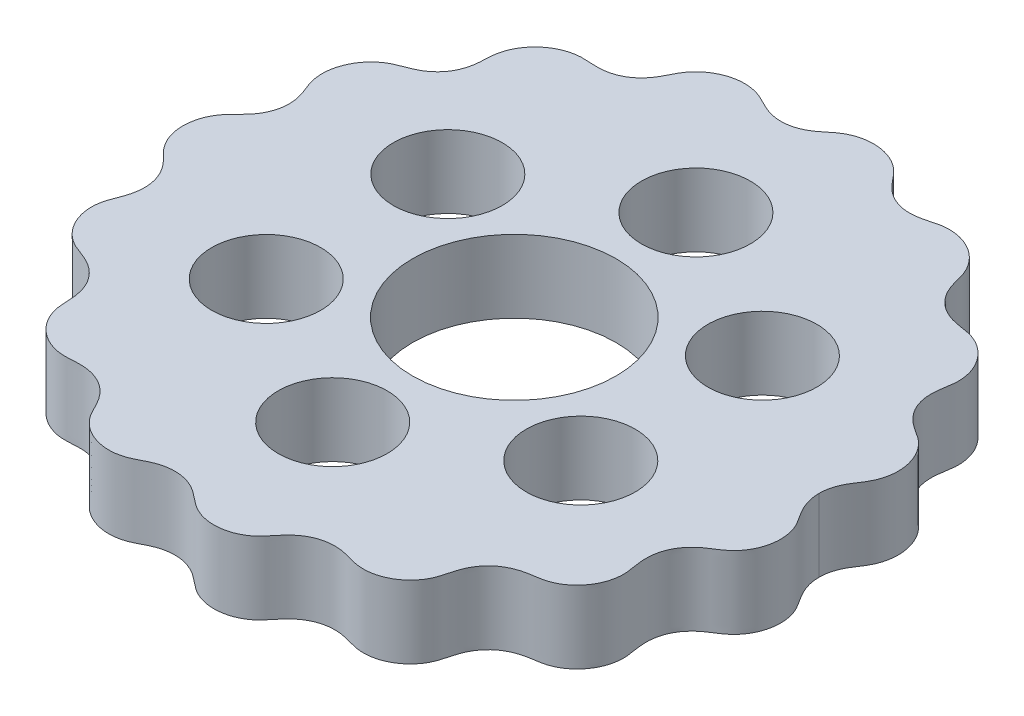
SolidWorks part; units mm, degrees
ref_plane "Front Plane" through (0, 0, 0) normal (0, 0, 1) x (1, 0, 0)
ref_plane "Top Plane" through (0, 0, 0) normal (0, 1, 0) x (1, 0, 0)
ref_plane "Right Plane" through (0, 0, 0) normal (1, 0, 0) x (0, 0, -1)
sketch "Sketch1" plane through (0, 0, 0) normal (0, 1, 0) x (1, 0, 0)
  spline S0 degree 4 poles (43.5597, 11.939) (43.7746, 11.6419) (44.1574, 11.0136) (44.5794, 10) (44.8033, 8.7434) (44.7975, 7.6608) (44.668, 6.827) (44.5095, 6.2289) (44.3102, 5.693) (44.0854, 5.2184) (43.8238, 4.7634) (43.5372, 4.324) (43.2453, 3.8884) (42.9654, 3.4447) (42.7296, 3.0237) (42.5376, 2.6274) (42.385, 2.2599) (42.266, 1.9245) (42.1655, 1.5834) (42.0842, 1.2366) (42.0304, 0.9309) (41.9969, 0.6642) (41.9795, 0.469) (41.9711, 0.3334) (41.9653, 0.1906) (41.9619, 0.0399) (41.9621, -0.0597) (41.9663, -0.2247) (41.9727, -0.3607) (41.9796, -0.4641) (41.9903, -0.5896) (42.0065, -0.7401) (42.0302, -0.9175) (42.0639, -1.118) (42.1042, -1.3174) (42.1625, -1.565) (42.2729, -1.9567) (42.4635, -2.4837) (42.7848, -3.1521) (43.2401, -3.8949) (43.7542, -4.6311) (44.2177, -5.4363) (44.5943, -6.4162) (44.8138, -7.5661) (44.8049, -8.865) (44.4957, -10.2551) (43.9377, -11.4628) (43.2043, -12.4546) (42.4647, -13.1309) (41.8318, -13.5688) (41.1811, -13.9778) (40.4339, -14.4637) (39.5457, -15.1906) (38.6597, -16.2863) (38.0157, -17.6823) (37.7592, -19.0784) (37.7936, -20.3757) (37.9921, -21.5309) (38.1706, -22.571) (38.1712, -23.7387) (37.9208, -24.9899) (37.3737, -26.2495) (36.6163, -27.2891) (35.8251, -28.0387) (35.0302, -28.5952) (34.2607, -28.9947) (33.3665, -29.3001) (32.3631, -29.4635) (31.4228, -29.5881) (30.5606, -29.7939) (29.7901, -30.0721) (29.1146, -30.4094) (28.3277, -30.9283) (27.4937, -31.6997) (26.786, -32.6963) (26.2692, -33.8909) (25.9676, -35.0401) (25.7097, -36.0924) (25.2353, -37.1812) (24.4955, -38.2338) (23.4754, -39.1756) (22.1893, -39.9181) (20.8637, -40.3306) (19.5822, -40.445) (18.4021, -40.3115) (17.3619, -40.0086) (16.2157, -39.6953) (14.9229, -39.5454) (13.5166, -39.678) (12.0834, -40.1877) (10.9215, -40.9607) (10.0286, -41.8586) (9.4107, -42.658) (8.9336, -43.2515) (8.4024, -43.7976) (7.7352, -44.3511) (6.7827, -44.906) (5.5039, -45.3361) (4.0459, -45.4914) (2.6815, -45.3353) (1.4727, -44.9266) (0.4618, -44.3422) (-0.3498, -43.6676) (-1.2509, -42.9181) (-2.3572, -42.2396) (-3.6945, -41.7638) (-5.2255, -41.6235) (-6.6175, -41.8429) (-7.6911, -42.2486) (-8.4854, -42.6528) (-9.165, -43.0118) (-9.8606, -43.341) (-10.8162, -43.6433) (-12.0419, -43.7826) (-13.3808, -43.6607) (-14.7658, -43.2208) (-15.9365, -42.5421) (-16.8664, -41.7061) (-17.4732, -40.8976) (-17.847, -40.2239) (-18.1868, -39.5337) (-18.5964, -38.7239) (-19.2403, -37.7358) (-20.2734, -36.7101) (-21.6552, -35.9123) (-23.06, -35.5304) (-24.2377, -35.4669) (-25.1438, -35.517) (-25.9114, -35.5679) (-26.6817, -35.5811) (-27.6854, -35.4598) (-28.8743, -35.0725) (-30.0474, -34.398) (-31.1208, -33.4185) (-31.8959, -32.3199) (-32.3881, -31.1887) (-32.6041, -30.21) (-32.6668, -29.443) (-32.6957, -28.675) (-32.7429, -27.785) (-32.9283, -26.6523) (-33.4342, -25.3372) (-34.3212, -24.0814) (-35.402, -23.1612) (-36.5427, -22.5423) (-37.6423, -22.1367) (-38.6323, -21.7712) (-39.644, -21.1879) (-40.6022, -20.3454) (-41.4197, -19.2418) (-42.0142, -17.9016) (-42.2811, -16.579) (-42.2768, -15.4767) (-42.1311, -14.6221) (-41.9237, -13.8891) (-41.6483, -13.1791) (-41.2649, -12.2442) (-40.9338, -11.0221) (-40.8452, -9.6292) (-41.1206, -8.1335) (-41.7086, -6.8487) (-42.4853, -5.8051) (-43.2328, -5.0626) (-43.819, -4.5014) (-44.2648, -3.9914) (-44.5868, -3.556) (-44.8456, -3.1297) (-45.0505, -2.7234) (-45.2099, -2.3436) (-45.3325, -1.9959) (-45.4219, -1.686) (-45.4858, -1.417) (-45.5305, -1.1911) (-45.5612, -1.0095) (-45.5868, -0.8269) (-45.6072, -0.643) (-45.6207, -0.4857) (-45.629, -0.3462) (-45.6347, -0.1984) (-45.6379, -0.0487) (-45.6379, 0.0472) (-45.6348, 0.1957) (-45.6292, 0.3418) (-45.6211, 0.48) (-45.608, 0.6354) (-45.588, 0.8169) (-45.563, 0.9975) (-45.5331, 1.1769) (-45.4894, 1.4002) (-45.427, 1.6661) (-45.3398, 1.9726) (-45.2201, 2.3165) (-45.0648, 2.6919) (-44.8655, 3.0933) (-44.614, 3.5146) (-44.3013, 3.9452) (-43.8679, 4.4506) (-43.2945, 5.0053) (-42.5505, 5.733) (-41.7653, 6.7558) (-41.1524, 8.0327) (-40.8866, 9.3506) (-40.8975, 10.5053) (-41.0269, 11.2688) (-41.1184, 11.6443) (-41.1703, 11.8304) knots 0 0 0 0 0 0.008246 0.016492 0.024485 0.028481 0.032478 0.035426 0.038375 0.041323 0.044272 0.04722 0.050168 0.053117 0.056065 0.058064 0.060064 0.062063 0.064062 0.066061 0.06806 0.069059 0.070059 0.070559 0.071058 0.072058 0.073216 0.073795 0.074374 0.074946 0.075518 0.076661 0.077805 0.078949 0.080092 0.081236 0.083523 0.088098 0.092673 0.097881 0.103089 0.108296 0.113504 0.121383 0.129262 0.137279 0.145296 0.151057 0.156819 0.159699 0.16258 0.168341 0.176861 0.18538 0.193962 0.202544 0.208469 0.214393 0.220317 0.226242 0.234568 0.242893 0.250927 0.254944 0.258961 0.264664 0.270368 0.276072 0.281775 0.286007 0.290239 0.294471 0.298703 0.307162 0.31562 0.321704 0.327787 0.33387 0.339954 0.348239 0.356525 0.36481 0.373096 0.379179 0.385262 0.391346 0.397429 0.405888 0.414347 0.42281 0.431274 0.436978 0.442681 0.445533 0.448385 0.454089 0.462122 0.470156 0.478482 0.486808 0.492732 0.498656 0.504581 0.510505 0.519087 0.527669 0.536189 0.544708 0.550469 0.55335 0.556231 0.561992 0.567753 0.57577 0.583787 0.591984 0.600181 0.605948 0.611715 0.614599 0.617482 0.623249 0.63212 0.640991 0.649862 0.658733 0.6645 0.667384 0.670267 0.676034 0.681801 0.689998 0.698195 0.706212 0.714229 0.719991 0.725752 0.728633 0.731513 0.737275 0.745794 0.754313 0.762895 0.771477 0.777402 0.783326 0.789251 0.795175 0.803501 0.811827 0.81986 0.827894 0.833598 0.83645 0.839301 0.845005 0.850709 0.859172 0.867636 0.876095 0.884554 0.890637 0.89672 0.899762 0.902804 0.905845 0.908887 0.910958 0.91303 0.915101 0.917172 0.918208 0.919244 0.92028 0.921315 0.922351 0.923387 0.923904 0.924422 0.925458 0.926481 0.926993 0.927504 0.928528 0.929551 0.930574 0.931597 0.93262 0.933643 0.93569 0.937736 0.939783 0.941829 0.944818 0.947808 0.950797 0.953787 0.959766 0.965745 0.974184 0.982624 0.991312 0.995656 1 1 1 1 1 construction
  spline S1 degree 4 poles (41.9625, 0) (41.9625, -0.0439) (41.9634, -0.1094) (41.9663, -0.2247) (41.9727, -0.3607) (41.9796, -0.4641) (41.9903, -0.5896) (42.0065, -0.7401) (42.0302, -0.9175) (42.0639, -1.118) (42.1042, -1.3174) (42.1625, -1.565) (42.2729, -1.9567) (42.4635, -2.4837) (42.7848, -3.1521) (43.2401, -3.8949) (43.7542, -4.6311) (44.2177, -5.4363) (44.5943, -6.4162) (44.8138, -7.5661) (44.8049, -8.865) (44.4957, -10.2551) (43.9377, -11.4628) (43.2043, -12.4546) (42.4647, -13.1309) (41.8318, -13.5688) (41.1811, -13.9778) (40.4339, -14.4637) (39.5457, -15.1906) (38.6597, -16.2863) (38.0157, -17.6823) (37.7592, -19.0784) (37.7936, -20.3757) (37.9921, -21.5309) (38.1706, -22.571) (38.1712, -23.7387) (37.9208, -24.9899) (37.3737, -26.2495) (36.6163, -27.2891) (35.8251, -28.0387) (35.0302, -28.5952) (34.2607, -28.9947) (33.3665, -29.3001) (32.3631, -29.4635) (31.4228, -29.5881) (30.5606, -29.7939) (29.7901, -30.0721) (29.1146, -30.4094) (28.3277, -30.9283) (27.4937, -31.6997) (26.786, -32.6963) (26.2692, -33.8909) (25.9676, -35.0401) (25.7097, -36.0924) (25.2353, -37.1812) (24.4955, -38.2338) (23.4754, -39.1756) (22.1893, -39.9181) (20.8637, -40.3306) (19.5822, -40.445) (18.4021, -40.3115) (17.3619, -40.0086) (16.2157, -39.6953) (14.9229, -39.5454) (13.5166, -39.678) (12.0834, -40.1877) (10.9215, -40.9607) (10.0286, -41.8586) (9.4107, -42.658) (8.9336, -43.2515) (8.4024, -43.7976) (7.7352, -44.3511) (6.7827, -44.906) (5.5039, -45.3361) (4.0459, -45.4914) (2.6815, -45.3353) (1.4727, -44.9266) (0.4618, -44.3422) (-0.3498, -43.6676) (-1.2509, -42.9181) (-2.3572, -42.2396) (-3.6945, -41.7638) (-5.2255, -41.6235) (-6.6175, -41.8429) (-7.6911, -42.2486) (-8.4854, -42.6528) (-9.165, -43.0118) (-9.8606, -43.341) (-10.8162, -43.6433) (-12.0419, -43.7826) (-13.3808, -43.6607) (-14.7658, -43.2208) (-15.9365, -42.5421) (-16.8664, -41.7061) (-17.4732, -40.8976) (-17.847, -40.2239) (-18.1868, -39.5337) (-18.5964, -38.7239) (-19.2403, -37.7358) (-20.2734, -36.7101) (-21.6552, -35.9123) (-23.06, -35.5304) (-24.2377, -35.4669) (-25.1438, -35.517) (-25.9114, -35.5679) (-26.6817, -35.5811) (-27.6854, -35.4598) (-28.8743, -35.0725) (-30.0474, -34.398) (-31.1208, -33.4185) (-31.8959, -32.3199) (-32.3881, -31.1887) (-32.6041, -30.21) (-32.6668, -29.443) (-32.6957, -28.675) (-32.7429, -27.785) (-32.9283, -26.6523) (-33.4342, -25.3372) (-34.3212, -24.0814) (-35.402, -23.1612) (-36.5427, -22.5423) (-37.6423, -22.1367) (-38.6323, -21.7712) (-39.644, -21.1879) (-40.6022, -20.3454) (-41.4197, -19.2418) (-42.0142, -17.9016) (-42.2811, -16.579) (-42.2768, -15.4767) (-42.1311, -14.6221) (-41.9237, -13.8891) (-41.6483, -13.1791) (-41.2649, -12.2442) (-40.9338, -11.0221) (-40.8452, -9.6292) (-41.1206, -8.1335) (-41.7086, -6.8487) (-42.4853, -5.8051) (-43.2328, -5.0626) (-43.819, -4.5014) (-44.2648, -3.9914) (-44.5868, -3.556) (-44.8456, -3.1297) (-45.0505, -2.7234) (-45.2099, -2.3436) (-45.3325, -1.9959) (-45.4219, -1.686) (-45.4858, -1.417) (-45.5305, -1.1911) (-45.5612, -1.0095) (-45.5868, -0.8269) (-45.6072, -0.643) (-45.6207, -0.4857) (-45.629, -0.3462) (-45.6347, -0.1984) (-45.6369, -0.0982) (-45.6375, -0.0393) (-45.6375, 0) knots 0.072058 0.072058 0.072058 0.072058 0.072058 0.073216 0.073795 0.074374 0.074946 0.075518 0.076661 0.077805 0.078949 0.080092 0.081236 0.083523 0.088098 0.092673 0.097881 0.103089 0.108296 0.113504 0.121383 0.129262 0.137279 0.145296 0.151057 0.156819 0.159699 0.16258 0.168341 0.176861 0.18538 0.193962 0.202544 0.208469 0.214393 0.220317 0.226242 0.234568 0.242893 0.250927 0.254944 0.258961 0.264664 0.270368 0.276072 0.281775 0.286007 0.290239 0.294471 0.298703 0.307162 0.31562 0.321704 0.327787 0.33387 0.339954 0.348239 0.356525 0.36481 0.373096 0.379179 0.385262 0.391346 0.397429 0.405888 0.414347 0.42281 0.431274 0.436978 0.442681 0.445533 0.448385 0.454089 0.462122 0.470156 0.478482 0.486808 0.492732 0.498656 0.504581 0.510505 0.519087 0.527669 0.536189 0.544708 0.550469 0.55335 0.556231 0.561992 0.567753 0.57577 0.583787 0.591984 0.600181 0.605948 0.611715 0.614599 0.617482 0.623249 0.63212 0.640991 0.649862 0.658733 0.6645 0.667384 0.670267 0.676034 0.681801 0.689998 0.698195 0.706212 0.714229 0.719991 0.725752 0.728633 0.731513 0.737275 0.745794 0.754313 0.762895 0.771477 0.777402 0.783326 0.789251 0.795175 0.803501 0.811827 0.81986 0.827894 0.833598 0.83645 0.839301 0.845005 0.850709 0.859172 0.867636 0.876095 0.884554 0.890637 0.89672 0.899762 0.902804 0.905845 0.908887 0.910958 0.91303 0.915101 0.917172 0.918208 0.919244 0.92028 0.921315 0.922351 0.923387 0.923904 0.924422 0.925458 0.925458 0.925458 0.925458 0.925458
  spline S2 degree 4 poles (41.9625, 0) (41.9625, 0.0414) (41.9633, 0.1025) (41.9661, 0.2136) (41.9723, 0.3429) (41.979, 0.4426) (41.9897, 0.5665) (42.0062, 0.718) (42.0307, 0.8955) (42.0657, 1.096) (42.1075, 1.2956) (42.1684, 1.543) (42.2836, 1.9343) (42.4832, 2.4588) (42.8173, 3.123) (43.2879, 3.8573) (43.7989, 4.5984) (44.24, 5.4185) (44.5952, 6.4079) (44.7975, 7.5628) (44.7792, 8.8653) (44.468, 10.2609) (43.9164, 11.4762) (43.1951, 12.4792) (42.3797, 13.2615) (41.536, 13.8395) (40.7187, 14.3311) (40.0042, 14.8629) (39.2678, 15.5586) (38.5743, 16.4697) (38.0112, 17.6915) (37.7741, 19.0918) (37.8343, 20.2538) (37.983, 21.1493) (38.0935, 21.7978) (38.1602, 22.3202) (38.1972, 22.9777) (38.1497, 23.8752) (37.9053, 24.9906) (37.3476, 26.2473) (36.479, 27.4364) (35.4716, 28.3359) (34.4158, 28.9579) (33.3732, 29.341) (32.3964, 29.5315) (31.4674, 29.6445) (30.6041, 29.8259) (29.8208, 30.0862) (29.1258, 30.4171) (28.324, 30.9344) (27.4862, 31.7122) (26.868, 32.6083) (26.4584, 33.5443) (26.2257, 34.284) (26.0891, 34.7989) (25.9592, 35.3151) (25.8112, 35.827) (25.5834, 36.453) (25.1805, 37.2695) (24.5041, 38.2095) (23.469, 39.1576) (22.1583, 39.9145) (20.8196, 40.3366) (19.6672, 40.4528) (18.759, 40.3928) (17.9711, 40.2551) (17.2007, 40.0427) (16.2002, 39.752) (14.921, 39.5729) (13.5083, 39.6859) (12.2436, 40.1383) (11.2701, 40.7519) (10.5091, 41.4277) (9.9205, 42.0847) (9.358, 42.8327) (8.7048, 43.5834) (7.8517, 44.2947) (6.7851, 44.898) (5.5023, 45.3208) (4.0383, 45.4784) (2.6711, 45.3331) (1.5829, 44.987) (0.7819, 44.5794) (0.2311, 44.2186) (-0.188, 43.8997) (-0.6945, 43.4797) (-1.3956, 42.9032) (-2.3718, 42.27) (-3.7031, 41.7753) (-5.0427, 41.652) (-6.1785, 41.7971) (-7.1492, 42.0869) (-7.967, 42.4398) (-8.8014, 42.9018) (-9.7238, 43.3435) (-10.809, 43.6585) (-12.0383, 43.7816) (-13.3837, 43.65) (-14.7797, 43.2067) (-15.9672, 42.5275) (-16.8213, 41.7781) (-17.3898, 41.0875) (-17.7487, 40.5393) (-18.0035, 40.0812) (-18.2955, 39.4951) (-18.6961, 38.6857) (-19.3181, 37.7092) (-20.3184, 36.7065) (-21.6483, 35.9387) (-23.0169, 35.5738) (-24.1734, 35.5233) (-25.0748, 35.5811) (-25.7283, 35.6213) (-26.2524, 35.6297) (-26.9067, 35.5929) (-27.789, 35.4459) (-28.8651, 35.081) (-30.047, 34.3922) (-31.1289, 33.4048) (-31.9156, 32.3055) (-32.4236, 31.1793) (-32.6934, 30.082) (-32.7721, 29.0623) (-32.7892, 28.1087) (-32.8925, 27.224) (-33.1269, 26.2384) (-33.5691, 25.1823) (-34.3457, 24.0838) (-35.4398, 23.1782) (-36.4763, 22.6494) (-37.3261, 22.3305) (-37.943, 22.1019) (-38.4287, 21.8984) (-39.0166, 21.6017) (-39.7701, 21.1118) (-40.6139, 20.3425) (-41.4234, 19.2311) (-42.0188, 17.8844) (-42.2941, 16.5622) (-42.3049, 15.3368) (-42.1154, 14.2423) (-41.792, 13.3012) (-41.4254, 12.4401) (-41.1507, 11.6019) (-40.946, 10.6049) (-40.9088, 9.644) (-41.0396, 8.6948) (-41.3322, 7.7909) (-41.6539, 7.1091) (-42.0994, 6.4068) (-42.6807, 5.7051) (-43.2972, 5.1143) (-43.8663, 4.5535) (-44.2937, 4.0418) (-44.6023, 3.6074) (-44.8524, 3.1814) (-45.0526, 2.7737) (-45.2101, 2.3898) (-45.3326, 2.0348) (-45.4219, 1.7185) (-45.4858, 1.4442) (-45.5305, 1.2138) (-45.5612, 1.0286) (-45.5868, 0.8429) (-45.6072, 0.6552) (-45.6207, 0.4934) (-45.629, 0.3539) (-45.6338, 0.2299) (-45.6363, 0.1285) (-45.6373, 0.0602) (-45.6375, 0.02) (-45.6375, 0) knots 0.07338 0.07338 0.07338 0.07338 0.07338 0.074472 0.075017 0.075563 0.076135 0.076707 0.07785 0.078994 0.080138 0.081281 0.082425 0.084712 0.089287 0.093861 0.099069 0.104277 0.109486 0.114694 0.122573 0.130452 0.138512 0.146571 0.152296 0.158021 0.163745 0.16947 0.173713 0.177956 0.186442 0.195001 0.203561 0.209467 0.212421 0.215374 0.218327 0.22128 0.227187 0.235488 0.24379 0.251894 0.259998 0.265567 0.271137 0.276706 0.282275 0.286582 0.290889 0.295197 0.299504 0.307939 0.316375 0.319362 0.32235 0.325338 0.328326 0.331314 0.334302 0.340277 0.348703 0.357129 0.365555 0.373981 0.379956 0.382944 0.385932 0.391908 0.397883 0.406319 0.414754 0.423368 0.427675 0.431982 0.437552 0.443121 0.44869 0.45426 0.462364 0.470468 0.478769 0.487071 0.492978 0.495931 0.498884 0.501837 0.50479 0.510697 0.519257 0.527816 0.536302 0.540545 0.544788 0.550513 0.556237 0.561962 0.567686 0.575746 0.583806 0.592068 0.60033 0.606208 0.609147 0.612086 0.615025 0.617964 0.623842 0.63236 0.640878 0.649396 0.657914 0.663792 0.666731 0.66967 0.672609 0.675548 0.681426 0.689688 0.69795 0.70601 0.714069 0.719794 0.725519 0.731243 0.736968 0.741211 0.745454 0.75394 0.762499 0.771059 0.776965 0.779919 0.782872 0.785825 0.788778 0.794685 0.802986 0.811288 0.819392 0.827496 0.833065 0.838635 0.844204 0.849773 0.85408 0.858388 0.867002 0.871219 0.875437 0.879655 0.883873 0.889848 0.895824 0.898812 0.9018 0.904787 0.907775 0.909882 0.911988 0.914095 0.916201 0.917254 0.918308 0.919361 0.920414 0.921467 0.92252 0.923047 0.923574 0.9241 0.924627 0.924627 0.924627 0.924627 0.924627
extrude "Boss-Extrude1" add sketch "Sketch1" along normal blind 10 contours S2 S1
sketch "Sketch2" plane through (0, 10, 0) normal (0, 1, 0) x (1, 0, 0)
  circle A0 centre (0, 0) radius 14
  circle A1 centre (0, 25) radius 7.5
  circle A7 centre (21.6506, 12.5) radius 7.5
  circle A8 centre (21.6506, -12.5) radius 7.5
  circle A9 centre (0, -25) radius 7.5
  circle A10 centre (-21.6506, -12.5) radius 7.5
  circle A11 centre (-21.6506, 12.5) radius 7.5
  point P17 (4.3301, -2.5)
  point P18 (0, 0)
  dimension "D1" = 28
  dimension "D2" = 15
  dimension "D3" = 25
  dimension "D4" = 6
extrude "Cut-Extrude1" cut sketch "Sketch2" against normal blind 10
